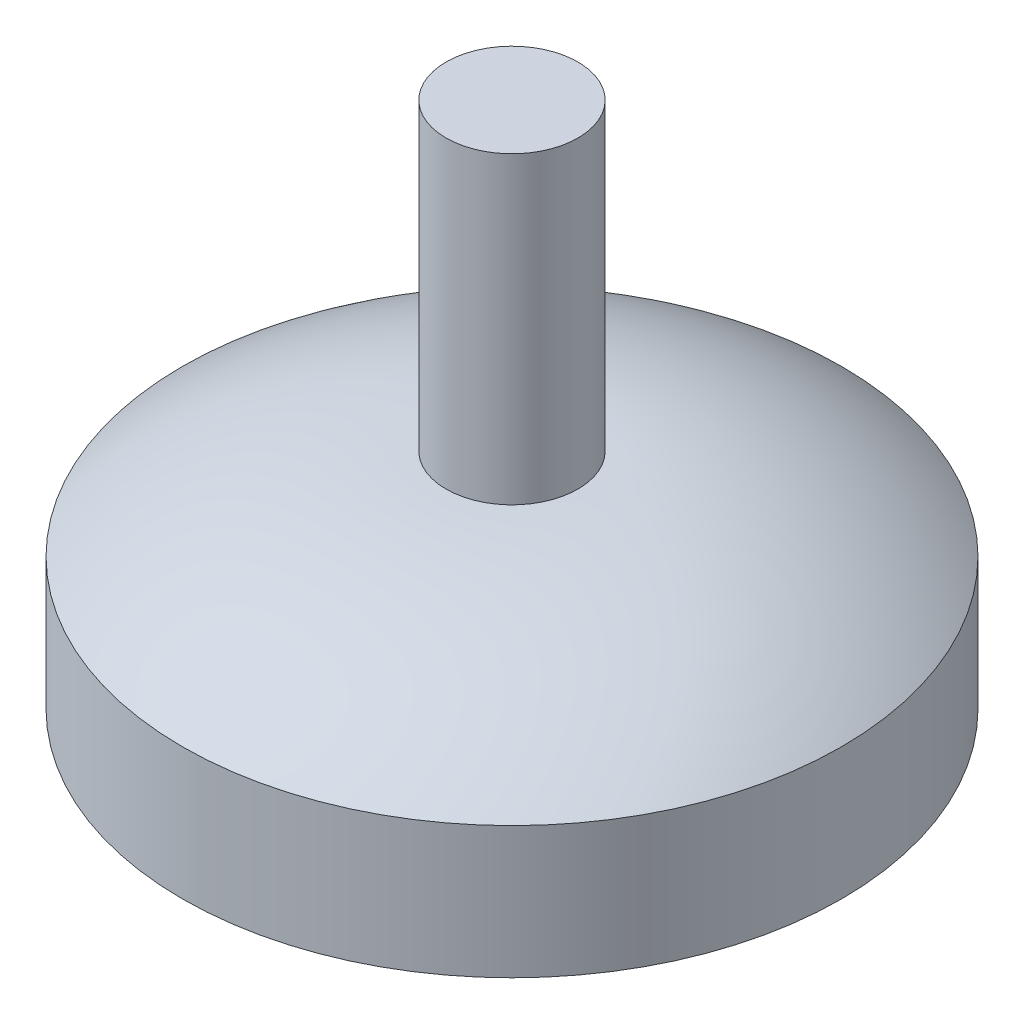
SolidWorks part; units mm, degrees
ref_plane "Alzado" through (0, 0, 0) normal (0, 0, 1) x (1, 0, 0)
ref_plane "Planta" through (0, 0, 0) normal (0, 1, 0) x (1, 0, 0)
ref_plane "Vista lateral" through (0, 0, 0) normal (1, 0, 0) x (0, 0, -1)
sketch "Croquis1" plane through (0, 0, 0) normal (0, 1, 0) x (1, 0, 0)
  circle A0 centre (0, 0) radius 25
  dimension "D1" = 50
extrude "Saliente-Extruir1" add sketch "Croquis1" along normal blind 10
sketch "Croquis2" plane through (0, 10, 0) normal (0, 1, 0) x (1, 0, 0)
  circle A0 centre (0, 0) radius 5
  dimension "D1" = 10
extrude "Saliente-Extruir2" add sketch "Croquis2" along normal blind 30
sketch "Croquis4" plane through (0, 0, 0) normal (0, 0, 1) x (1, 0, 0)
  line L0 (5, 10) -> (5, 40) construction
  line L1 (5, 16.9317) -> (5, 10)
  line L2 (5, 10) -> (25, 10)
  spline S0 degree 2 poles (25, 10) (16.2337, 16.9317) (5, 16.9317) knots 0 0 0 1 1 1
revolve "Revolución1" add sketch "Croquis4" angle 360 about axis through (0, 40, 0) along (0, -1, 0)
